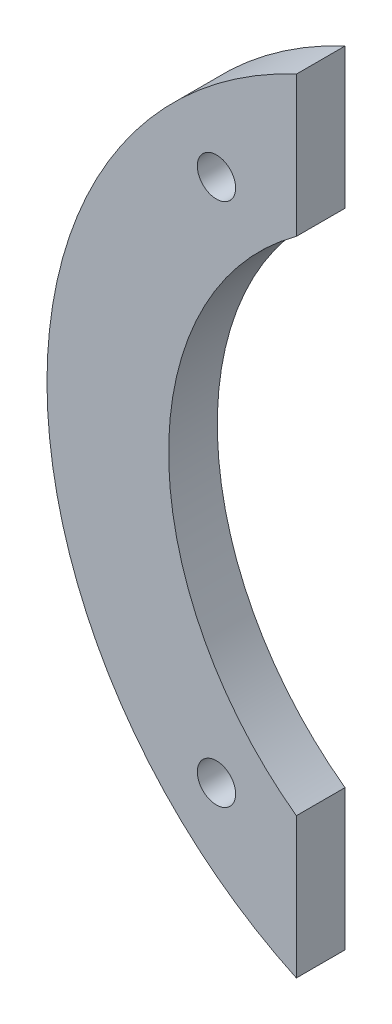
SolidWorks part; units mm, degrees
ref_plane "前视基准面" through (0, 0, 0) normal (0, 0, 1) x (1, 0, 0)
ref_plane "上视基准面" through (0, 0, 0) normal (0, 1, 0) x (1, 0, 0)
ref_plane "右视基准面" through (0, 0, 0) normal (1, 0, 0) x (0, 0, -1)
other "Configuration Table"
sketch "草图1" plane through (0, 0, 0) normal (0, 0, 1) x (1, 0, 0)
  circle A0 centre (0, 0) radius 25.5
  circle A1 centre (0, 0) radius 35.5
  dimension "D1" = 51
  dimension "D2" = 71
extrude "凸台-拉伸1" add sketch "草图1" along normal blind 4
sketch "草图2" plane through (0, 0, 4) normal (0, 0, 1) x (1, 0, 0)
  line L0 (0, 0) -> (-21.5668, 21.5668) construction
  line L1 (0, 0) -> (-35.5, 0) construction
  circle A0 centre (-21.5668, 21.5668) radius 1.575
  circle A1 centre (0, 0) radius 35.5 construction
  circle A2 centre (21.5668, 21.5668) radius 1.575
  circle A3 centre (21.5668, -21.5668) radius 1.575
  circle A4 centre (-21.5668, -21.5668) radius 1.575
  point P3 (0, 0)
  point P9 (21.5668, 21.5668)
  point P17 (0, 0)
  dimension "D1" = 3.15
  dimension "D2" = 30.5
  dimension "D3" = 45
  dimension "D4" = 4
extrude "切除-拉伸1" cut sketch "草图2" against normal through all
sketch "草图3" plane through (0, 0, 4) normal (0, 0, 1) x (1, 0, 0)
  line L1 (-15, 40) -> (45, 40)
  line L2 (-15, 40) -> (-15, -40)
  line L3 (-15, -40) -> (45, -40)
  line L4 (45, 40) -> (45, -40)
  dimension "D1" = 15
  dimension "D2" = 60
  dimension "D3" = 40
  dimension "D4" = 40
extrude "切除-拉伸2" cut sketch "草图3" against normal through all
